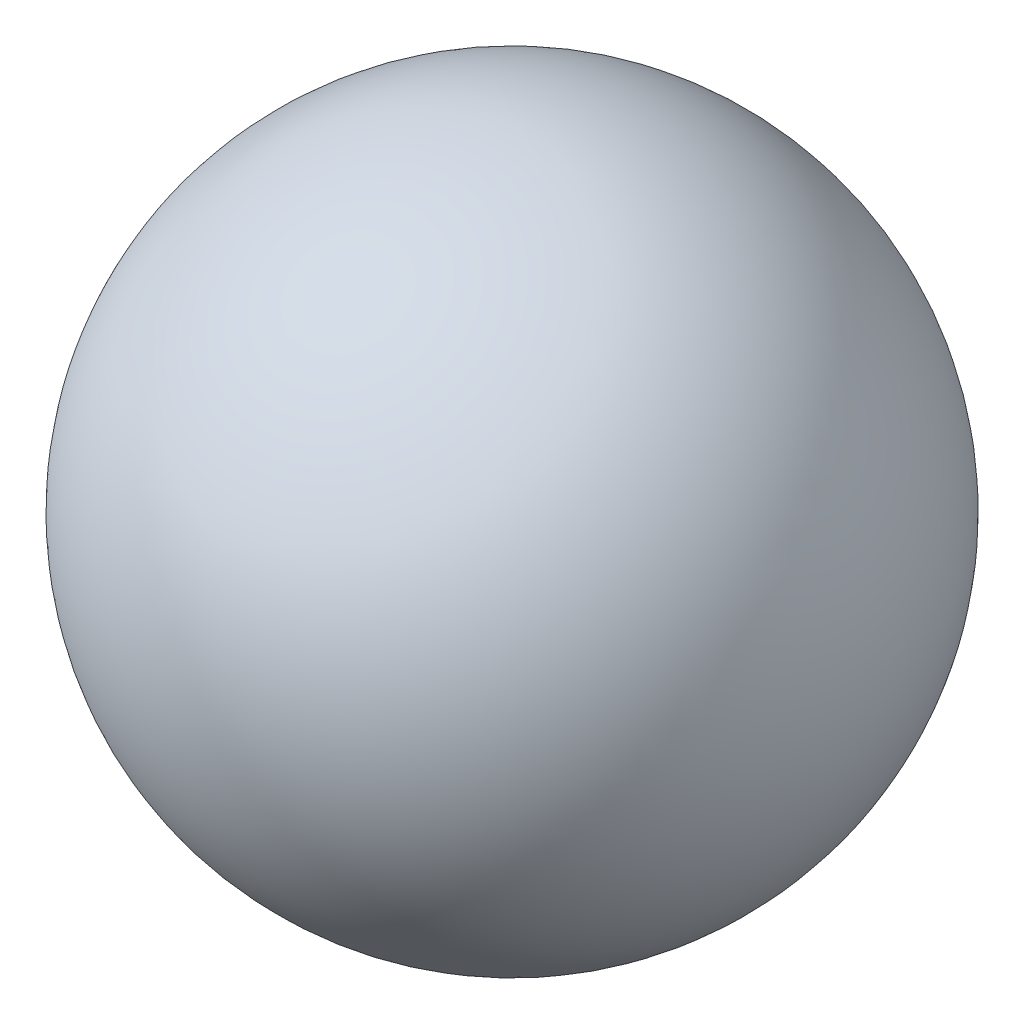
SolidWorks part; units mm, degrees
ref_plane "前视基准面" through (0, 0, 0) normal (0, 0, 1) x (1, 0, 0)
ref_plane "上视基准面" through (0, 0, 0) normal (0, 1, 0) x (1, 0, 0)
ref_plane "右视基准面" through (0, 0, 0) normal (1, 0, 0) x (0, 0, -1)
other "Configuration Table"
sketch "草图1" plane through (0, 0, 0) normal (0, 0, 1) x (1, 0, 0)
  line L0 (0, 0) -> (16, 0) construction
  line L1 (0, 0) -> (-44.9894, 0) construction
  line L2 (16, 0) -> (-16, 0)
  arc A0 (16, 0) -> (-16, 0) centre (0, 0) ccw
  dimension "D1" = 16
revolve "旋转6" add sketch "草图1" angle 360 about L2
